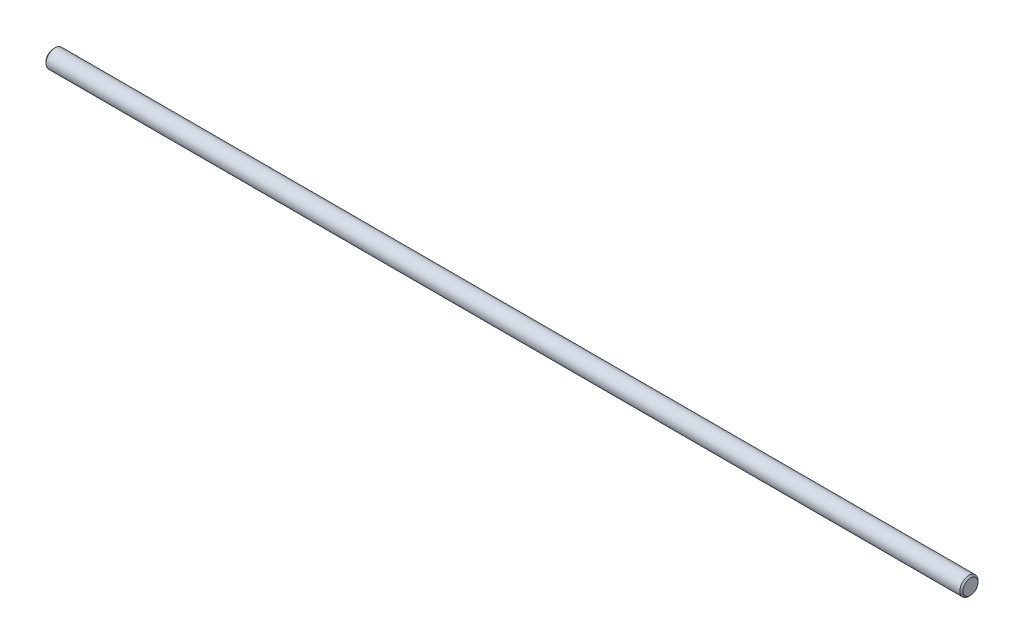
SolidWorks part; units mm, degrees
ref_plane "Alzado" through (0, 0, 0) normal (0, 0, 1) x (1, 0, 0)
ref_plane "Planta" through (0, 0, 0) normal (0, 1, 0) x (1, 0, 0)
ref_plane "Vista lateral" through (0, 0, 0) normal (1, 0, 0) x (0, 0, -1)
sketch "Croquis1" plane through (419.9152, 0, 0) normal (1, 0, 0) x (0, 0, -1)
  circle A2 centre (158.8387, -27.5) radius 3
  dimension "D1" = 6
extrude "Saliente-Extruir1" add sketch "Croquis1" against normal up to surface (303.5 mm away)
chamfer "Chaflán1" distance 0.5 angle 45 2 edges at (419.9152, -27.5, -161.8387) (116.4152, -27.5, -155.8387)
